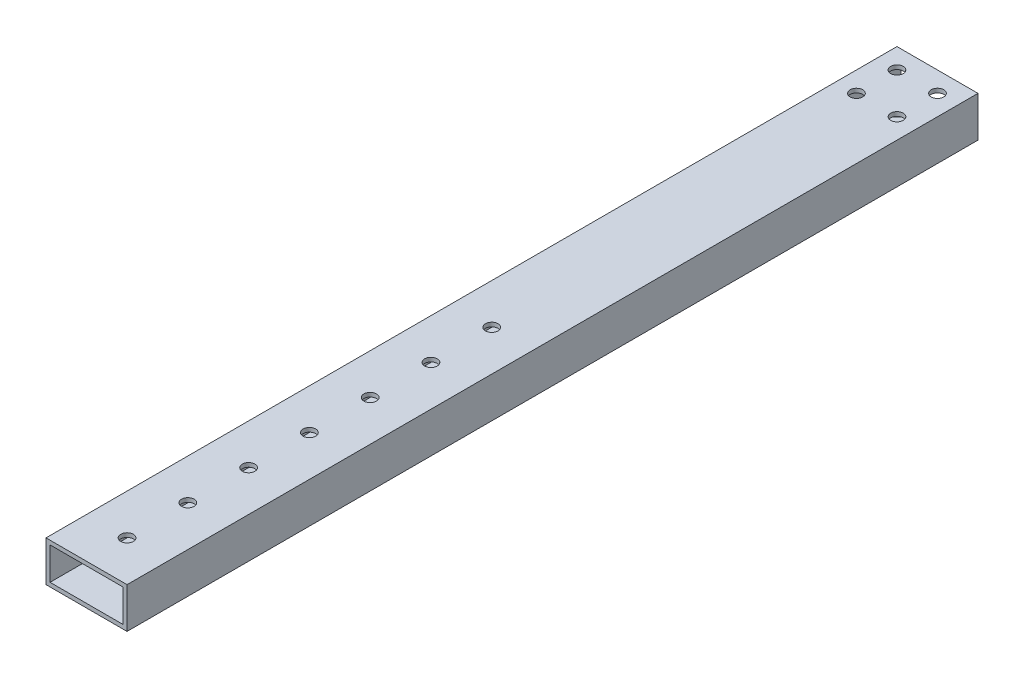
SolidWorks part; units mm, degrees
material "Thornel Mat VMA"
ref_plane "前视基准面" through (0, 0, 0) normal (0, 0, 1) x (1, 0, 0)
ref_plane "上视基准面" through (0, 0, 0) normal (0, 1, 0) x (1, 0, 0)
ref_plane "右视基准面" through (0, 0, 0) normal (1, 0, 0) x (0, 0, -1)
other "Configuration Table"
sketch "草图1" plane through (0, 0, 0) normal (0, 0, 1) x (1, 0, 0)
  line L0 (1, 1) -> (1, 9)
  line L1 (0, 0) -> (20, 0)
  line L2 (0, 0) -> (0, 10)
  line L3 (0, 10) -> (20, 10)
  line L4 (20, 0) -> (20, 10)
  line L5 (1, 9) -> (19, 9)
  line L6 (19, 1) -> (19, 9)
  line L7 (1, 1) -> (19, 1)
  dimension "D1" = 10
  dimension "D2" = 20
  dimension "D3" = 1
extrude "凸台-拉伸1" add sketch "草图1" along normal blind 210
sketch "草图2" plane through (0, 0, 0) normal (0, -1, 0) x (1, 0, 0)
  line L0 (0, 210) -> (0, 0) construction
  line L1 (0, 0) -> (20, 0) construction
  circle A0 centre (5, 5) radius 1.55
  circle A1 centre (15, 5) radius 1.55
  circle A2 centre (15, 15) radius 1.55
  circle A3 centre (5, 15) radius 1.55
  dimension "D2" = 3.1
  dimension "D1" = 5
  dimension "D3" = 5
  dimension "D4" = 2
  dimension "D5" = 2
extrude "切除-拉伸1" cut sketch "草图2" against normal through all
sketch "草图3" plane through (0, 0, 0) normal (0, -1, 0) x (1, 0, 0)
  line L0 (10, 0) -> (10, 210) construction
  line L1 (0, 0) -> (20, 0) construction
  line L2 (0, 210) -> (20, 210) construction
  circle A0 centre (10, 200) radius 1.55
  circle A4 centre (10, 185) radius 1.55
  circle A5 centre (10, 170) radius 1.55
  circle A6 centre (10, 155) radius 1.55
  circle A7 centre (10, 140) radius 1.55
  circle A8 centre (10, 125) radius 1.55
  circle A9 centre (10, 110) radius 1.55
  dimension "D1" = 10
  dimension "D2" = 3.1
  dimension "D3" = 7
extrude "切除-拉伸2" cut sketch "草图3" against normal through all
